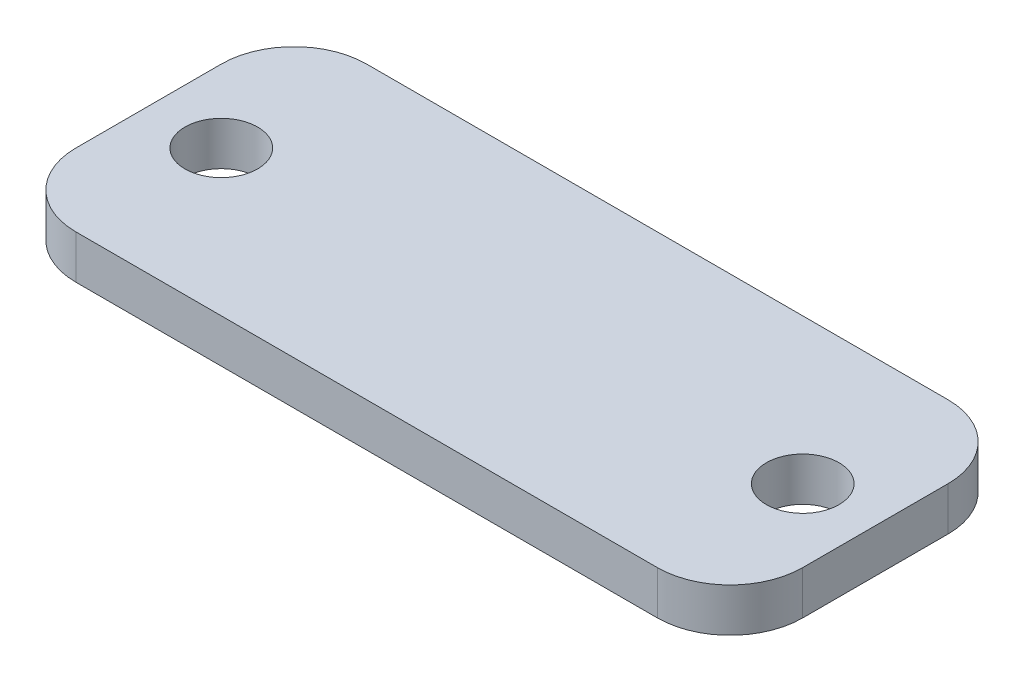
SolidWorks part; units mm, degrees
ref_plane "Front Plane" through (0, 0, 0) normal (0, 0, 1) x (1, 0, 0)
ref_plane "Top Plane" through (0, 0, 0) normal (0, 1, 0) x (1, 0, 0)
ref_plane "Right Plane" through (0, 0, 0) normal (1, 0, 0) x (0, 0, -1)
sketch "Sketch1" plane through (0, 0, 0) normal (0, 1, 0) x (1, 0, 0)
  line L1 (-25, -10) -> (25, -10)
  line L2 (-25, -10) -> (-25, 10)
  line L3 (-25, 10) -> (25, 10)
  line L4 (25, -10) -> (25, 10)
  line L5 (-25, -10) -> (25, 10) construction
  line L6 (-25, 10) -> (25, -10) construction
  circle A0 centre (20, 0) radius 2.5
  circle A1 centre (-20, 0) radius 2.5
  point P0 (0, 0)
  dimension "D3" = 5
  dimension "D4" = 40
  dimension "D5" = 20
  dimension "D1" = 50
  dimension "D2" = 20
extrude "Boss-Extrude1" add sketch "Sketch1" along normal blind 3
fillet "Fillet1" radius 5 4 edges at (-25, 1.5, 10) (-25, 1.5, -10) (25, 1.5, 10) (25, 1.5, -10)
